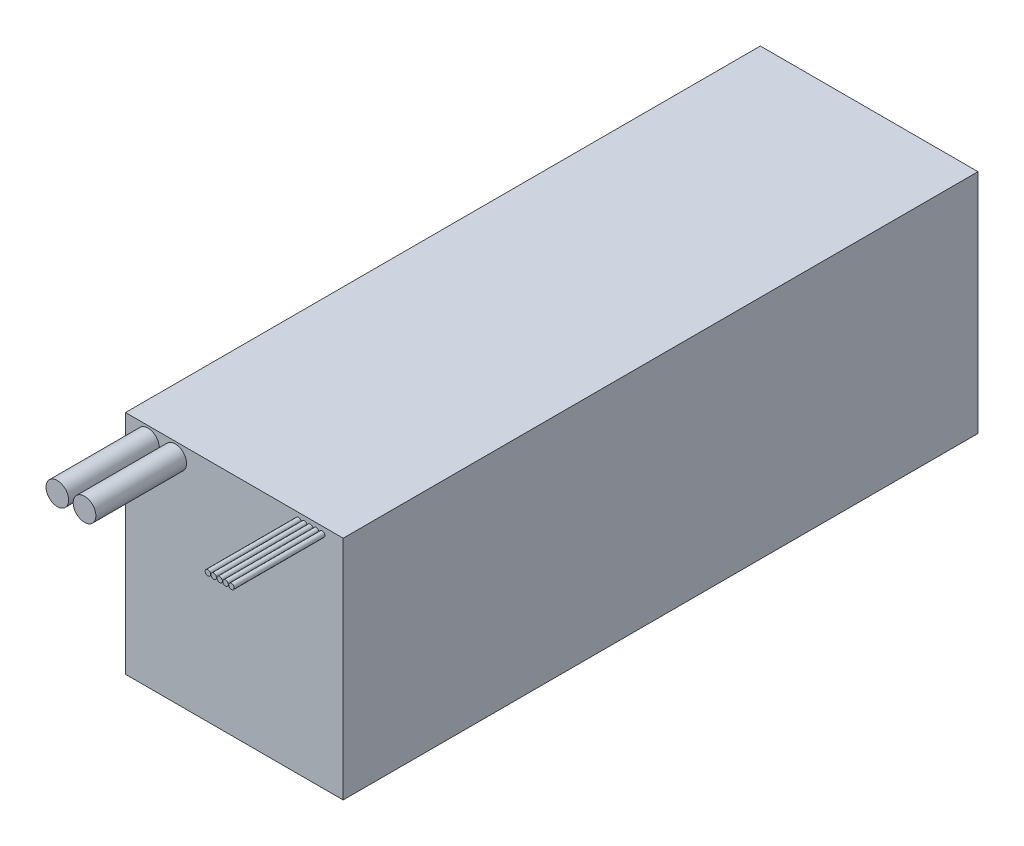
SolidWorks part; units mm, degrees
ref_plane "Plan de face" through (0, 0, 0) normal (0, 0, 1) x (1, 0, 0)
ref_plane "Plan de dessus" through (0, 0, 0) normal (0, 1, 0) x (1, 0, 0)
ref_plane "Plan de droite" through (0, 0, 0) normal (1, 0, 0) x (0, 0, -1)
sketch "Esquisse1" plane through (0, 0, 0) normal (0, 0, 1) x (1, 0, 0)
  line L1 (-24, 25) -> (24, 25)
  line L2 (-24, 25) -> (-24, -25)
  line L3 (-24, -25) -> (24, -25)
  line L4 (24, 25) -> (24, -25)
  point P4 (0, 25)
  point P6 (-24, 0)
  dimension "D1" = 48
  dimension "D2" = 50
extrude "Boss.-Extru.1" add sketch "Esquisse1" along normal mid plane 140
sketch "Esquisse2" plane through (0, 0, 70) normal (0, 0, 1) x (1, 0, 0)
  line L0 (24, 25) -> (-24, 25) construction
  circle A0 centre (-19.0391, 22) radius 2.5
  circle A1 centre (-13.0391, 22) radius 2.5
  circle A2 centre (14.1644, 23.4803) radius 0.6
  circle A7 centre (15.4644, 23.4803) radius 0.6
  circle A8 centre (16.7644, 23.4803) radius 0.6
  circle A9 centre (18.0644, 23.4803) radius 0.6
  circle A10 centre (19.3644, 23.4803) radius 0.6
  dimension "D1" = 5
  dimension "D2" = 1.2
  dimension "D4" = 3
  dimension "D5" = 6
  dimension "D3" = 5
extrude "Boss.-Extru.2" add sketch "Esquisse2" along normal blind 20 contours A0 | A1 | A7 | A8 | A9 | A10 | A2
